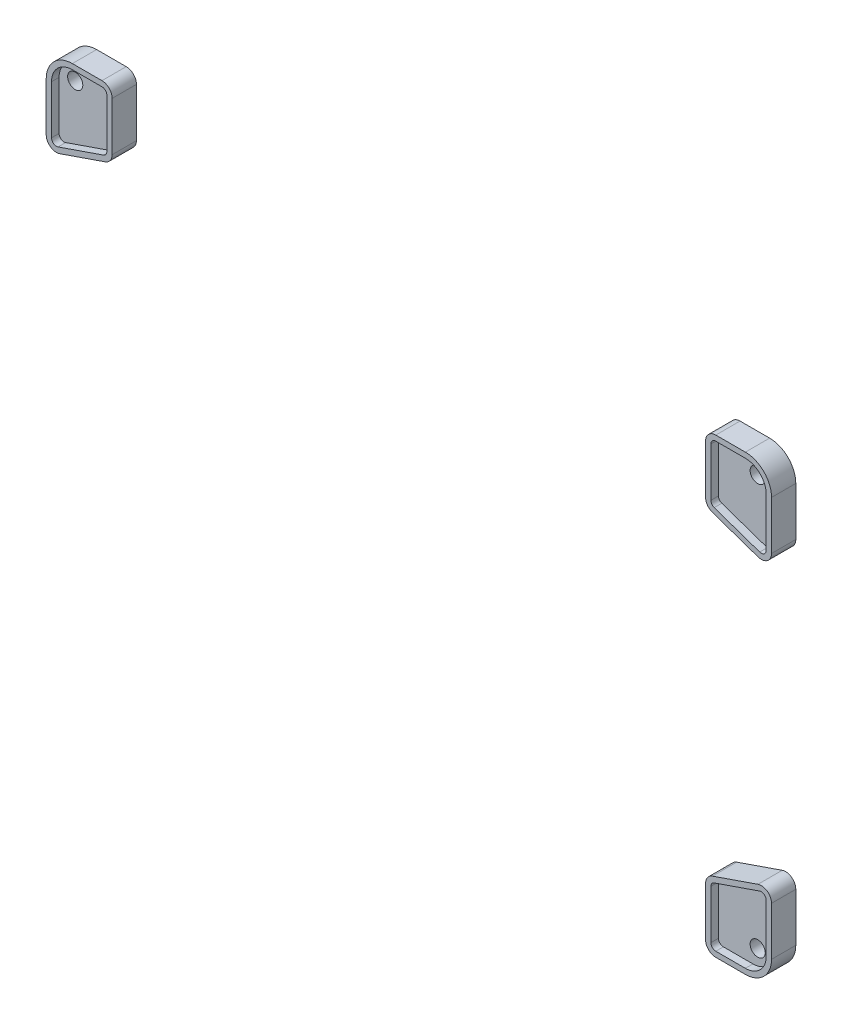
SolidWorks part; units mm, degrees
ref_plane "Front Plane" through (0, 0, 0) normal (0, 0, 1) x (1, 0, 0)
ref_plane "Top Plane" through (0, 0, 0) normal (0, 1, 0) x (1, 0, 0)
ref_plane "Right Plane" through (0, 0, 0) normal (1, 0, 0) x (0, 0, -1)
sketch "Sketch1" plane through (0, 0, 0) normal (0, 0, 1) x (1, 0, 0)
  line L0 (47.825, 19.975) -> (47.825, 26.375)
  line L1 (44.375, 29.825) -> (40.475, 29.825)
  line L2 (39.125, 28.475) -> (39.125, 22.0444)
  line L3 (40.0348, 20.7681) -> (46.0348, 18.6988)
  line L4 (47.975, 19.975) -> (47.975, 26.375)
  line L5 (44.375, 29.975) -> (40.475, 29.975)
  line L6 (38.975, 28.475) -> (38.975, 22.0444)
  line L7 (39.9859, 20.6263) -> (45.9859, 18.557)
  line L8 (47.975, 19.975) -> (47.975, 26.375) construction
  line L9 (44.375, 29.975) -> (40.475, 29.975) construction
  line L10 (38.975, 28.475) -> (38.975, 22.0444) construction
  line L11 (39.9859, 20.6263) -> (45.9859, 18.557) construction
  arc A0 (47.825, 26.375) -> (44.375, 29.825) centre (44.375, 26.375) ccw
  arc A1 (40.475, 29.825) -> (39.125, 28.475) centre (40.475, 28.475) ccw
  arc A2 (39.125, 22.0444) -> (40.0348, 20.7681) centre (40.475, 22.0444) ccw
  arc A3 (46.0348, 18.6988) -> (47.825, 19.975) centre (46.475, 19.975) ccw
  arc A4 (45.9859, 18.557) -> (47.975, 19.975) centre (46.475, 19.975) ccw
  arc A5 (47.975, 26.375) -> (44.375, 29.975) centre (44.375, 26.375) ccw
  arc A6 (40.475, 29.975) -> (38.975, 28.475) centre (40.475, 28.475) ccw
  arc A7 (38.975, 22.0444) -> (39.9859, 20.6263) centre (40.475, 22.0444) ccw
  arc A8 (45.9859, 18.557) -> (47.975, 19.975) centre (46.475, 19.975) ccw construction
  arc A9 (47.975, 26.375) -> (44.375, 29.975) centre (44.375, 26.375) ccw construction
  arc A10 (40.475, 29.975) -> (38.975, 28.475) centre (40.475, 28.475) ccw construction
  arc A11 (38.975, 22.0444) -> (39.9859, 20.6263) centre (40.475, 22.0444) ccw construction
  point P24 (39.5204, 29.4296)
  point P25 (47.2587, 18.8757)
  point P26 (46.8145, 28.8145)
  point P27 (39.3757, 21.2607)
  dimension "D7" = 1.35
  dimension "D5" = 8.7
  dimension "D6" = 9.0569
  dimension "D1" = 0
  dimension "D2" = 0.15
extrude "Boss-Extrude1" add sketch "Sketch1" along normal blind 3.2
sketch "Sketch2" plane through (0, 0, 3.2) normal (0, 0, 1) x (1, 0, 0)
  line L0 (47.125, 19.975) -> (47.125, 26.375)
  line L1 (44.375, 29.125) -> (40.475, 29.125)
  line L2 (39.825, 28.475) -> (39.825, 22.0444)
  line L3 (40.2631, 21.4299) -> (46.2631, 19.3605)
  line L4 (47.825, 19.975) -> (47.825, 26.375)
  line L5 (44.375, 29.825) -> (40.475, 29.825)
  line L6 (39.125, 28.475) -> (39.125, 22.0444)
  line L7 (40.0348, 20.7681) -> (46.0348, 18.6988)
  line L8 (47.825, 19.975) -> (47.825, 26.375)
  line L9 (44.375, 29.825) -> (40.475, 29.825)
  line L10 (39.125, 28.475) -> (39.125, 22.0444)
  line L11 (40.0348, 20.7681) -> (46.0348, 18.6988)
  arc A0 (47.125, 26.375) -> (44.375, 29.125) centre (44.375, 26.375) ccw
  arc A1 (40.475, 29.125) -> (39.825, 28.475) centre (40.475, 28.475) ccw
  arc A2 (39.825, 22.0444) -> (40.2631, 21.4299) centre (40.475, 22.0444) ccw
  arc A3 (46.2631, 19.3605) -> (47.125, 19.975) centre (46.475, 19.975) ccw
  arc A4 (46.0348, 18.6988) -> (47.825, 19.975) centre (46.475, 19.975) ccw
  arc A5 (47.825, 26.375) -> (44.375, 29.825) centre (44.375, 26.375) ccw
  arc A6 (40.475, 29.825) -> (39.125, 28.475) centre (40.475, 28.475) ccw
  arc A7 (39.125, 22.0444) -> (40.0348, 20.7681) centre (40.475, 22.0444) ccw
  arc A8 (46.0348, 18.6988) -> (47.825, 19.975) centre (46.475, 19.975) ccw
  arc A9 (47.825, 26.375) -> (44.375, 29.825) centre (44.375, 26.375) ccw
  arc A10 (40.475, 29.825) -> (39.125, 28.475) centre (40.475, 28.475) ccw
  arc A11 (39.125, 22.0444) -> (40.0348, 20.7681) centre (40.475, 22.0444) ccw
  dimension "D1" = 0
  dimension "D2" = 0.7
extrude "Cut-Extrude1" cut sketch "Sketch2" against normal blind 1 contours L3 A3 L0 A0 L1 A1 L2 A2
sketch "Sketch4" plane through (0, 0, 0) normal (0, 0, -1) x (-1, 0, 0)
  circle A0 centre (-45, 27.04) radius 0.8 construction
  circle A1 centre (-45, 27.04) radius 1
  circle A2 centre (-45, 27.04) radius 0.8 construction
  dimension "D3" = 2
extrude "Cut-Extrude2" cut sketch "Sketch4" against normal through all
mirror "Mirror2" about plane through (0, 0, 0) normal (0, 1, 0) of bodies 103
mirror "Mirror3" about plane through (0, 0, 0) normal (1, 0, 0) of bodies 103
